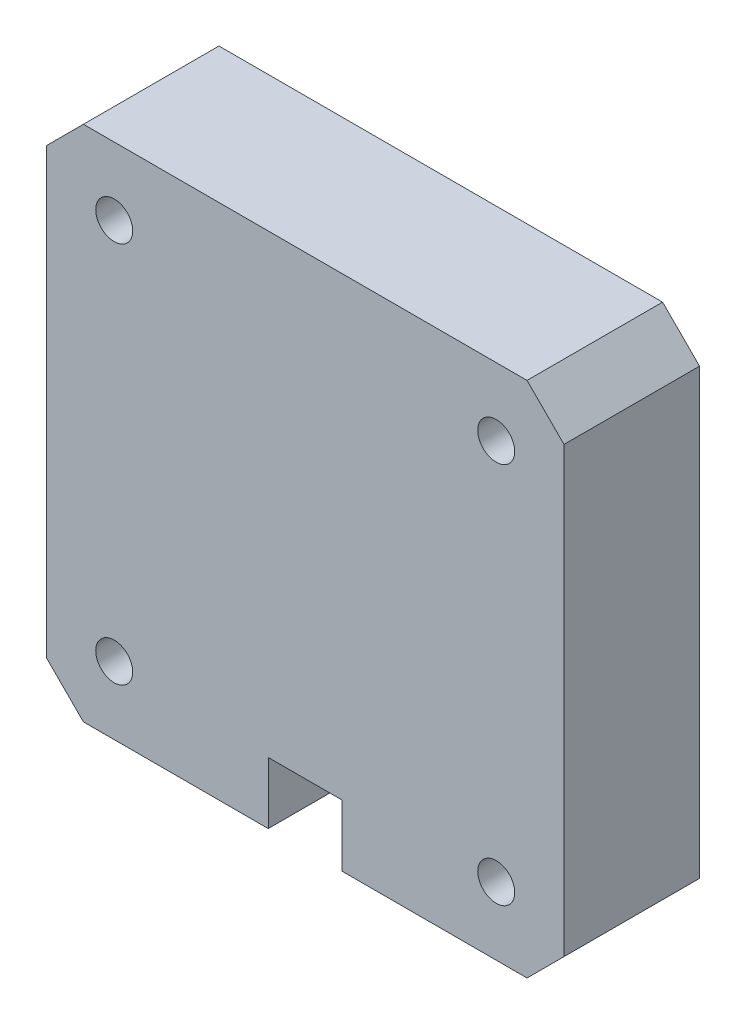
SolidWorks part; units mm, degrees
ref_plane "Front Plane" through (0, 0, 0) normal (0, 0, 1) x (1, 0, 0)
ref_plane "Top Plane" through (0, 0, 0) normal (0, 1, 0) x (1, 0, 0)
ref_plane "Right Plane" through (0, 0, 0) normal (1, 0, 0) x (0, 0, -1)
sketch "Sketch1" plane through (0, 0, 0) normal (0, 0, 1) x (1, 0, 0)
  line L1 (-21, 21) -> (21, 21)
  line L2 (-21, 21) -> (-21, -21)
  line L3 (-21, -21) -> (21, -21)
  line L4 (21, 21) -> (21, -21)
  line L5 (-21, 21) -> (21, -21) construction
  line L6 (-21, -21) -> (21, 21) construction
  point P0 (0, 0)
  dimension "D1" = 42
  dimension "D2" = 42
extrude "Boss-Extrude1" add sketch "Sketch1" along normal blind 11 contours L1 L4 L3 L2
chamfer "Chamfer1" distance 3 angle 45 4 edges at (21, -21, 5.5) (-21, -21, 5.5) (-21, 21, 5.5) (21, 21, 5.5)
sketch "Sketch3" plane through (0, 0, 0) normal (0, 0, -1) x (-1, 0, 0)
  line L1 (-15.5, 15.5) -> (15.5, 15.5) construction
  line L2 (-15.5, 15.5) -> (-15.5, -15.5) construction
  line L3 (-15.5, -15.5) -> (15.5, -15.5) construction
  line L4 (15.5, 15.5) -> (15.5, -15.5) construction
  line L5 (-15.5, 15.5) -> (15.5, -15.5) construction
  line L6 (-15.5, -15.5) -> (15.5, 15.5) construction
  circle A0 centre (-15.5, 15.5) radius 1.5
  circle A1 centre (15.5, 15.5) radius 1.5
  circle A2 centre (15.5, -15.5) radius 1.5
  circle A3 centre (-15.5, -15.5) radius 1.5
  point P0 (0, 0)
  dimension "D3" = 3
  dimension "D1" = 31
  dimension "D2" = 31
extrude "Cut-Extrude2" cut sketch "Sketch3" against normal up to next
sketch "Sketch4" plane through (0, 0, 0) normal (0, 0, -1) x (-1, 0, 0)
  circle A0 centre (-15.5, 15.5) radius 2.85
  circle A1 centre (15.5, 15.5) radius 2.85
  circle A2 centre (15.5, -15.5) radius 2.85
  circle A3 centre (-15.5, -15.5) radius 2.85
  dimension "D1" = 5.7
extrude "Cut-Extrude3" cut sketch "Sketch4" against normal blind 3
sketch "Sketch5" plane through (0, -21, 0) normal (0, -1, 0) x (1, 0, 0)
  line L0 (-18, 11) -> (18, 11) construction
  line L1 (3, 4) -> (-3, 4)
  line L2 (3, 4) -> (3, 11)
  line L3 (3, 11) -> (-3, 11)
  line L4 (-3, 4) -> (-3, 11)
  point P6 (0, 4)
  dimension "D1" = 7
  dimension "D2" = 6
extrude "Cut-Extrude4" cut sketch "Sketch5" against normal blind 5
